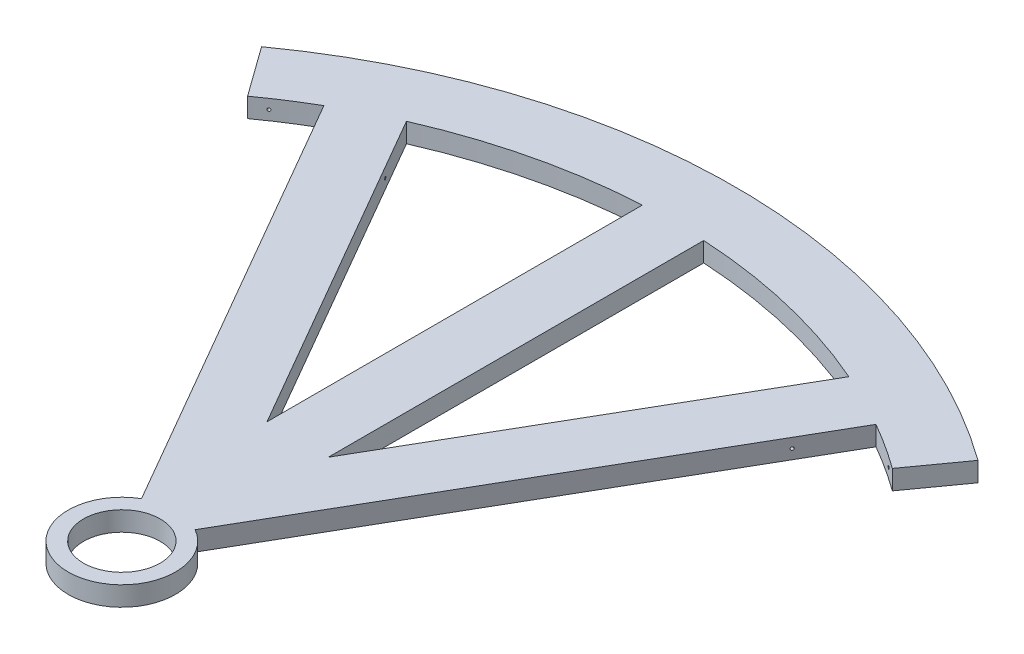
SolidWorks part; units mm, degrees
ref_plane "Front Plane" through (0, 0, 0) normal (0, 0, 1) x (1, 0, 0)
ref_plane "Top Plane" through (0, 0, 0) normal (0, 1, 0) x (1, 0, 0)
ref_plane "Right Plane" through (0, 0, 0) normal (1, 0, 0) x (0, 0, -1)
sketch "Sketch1" plane through (0, 0, 0) normal (0, 1, 0) x (1, 0, 0)
  line L0 (-90, -17.3205) -> (0, -173.2051)
  line L1 (0, -173.2051) -> (90, -17.3205)
  line L2 (-100, 0) -> (100, 0) construction
  line L3 (-72.1222, -8.2857) -> (-10, -115.8846)
  line L4 (10, -115.8846) -> (72.1222, -8.2857)
  line L5 (82.1782, 9.1318) -> (82.6795, 10)
  line L6 (0, -133.2051) -> (82.6795, 10) construction
  line L7 (-10, 6.5169) -> (-10, -115.8846)
  line L8 (10, -115.8846) -> (10, 6.5169)
  line L9 (-72.1222, -8.2857) -> (0, -133.2051) construction
  line L10 (-105.119, -27.0887) -> (-116.7988, -10.8535)
  line L11 (105.119, -27.0887) -> (116.7988, -10.8535)
  line L12 (-100, 0) -> (0, -173.2051) construction
  line L13 (0, -173.2051) -> (100, 0) construction
  arc A0 (-100, 0) -> (100, 0) centre (0, -173.2051) cw
  arc A1 (-72.1222, -8.2857) -> (-10, 6.5169) centre (0, -173.2051) cw
  arc A2 (-72.1222, -8.2857) -> (90, -17.3205) centre (0, -173.2051) cw construction
  arc A3 (10, 6.5169) -> (72.1222, -8.2857) centre (0, -173.2051) cw
  arc A4 (100, 0) -> (116.7988, -10.8535) centre (0, -173.2051) cw
  arc A5 (-100, 0) -> (-116.7988, -10.8535) centre (0, -173.2051) ccw
  arc A6 (-90, -17.3205) -> (-105.119, -27.0887) centre (0, -173.2051) ccw
  arc A7 (90, -17.3205) -> (105.119, -27.0887) centre (0, -173.2051) cw
  circle A8 centre (0, -173.2051) radius 12.5
  circle A9 centre (0, -173.2051) radius 17.5
  point P2 (0, 0)
  dimension "D6" = 20
  dimension "D9" = 25
  dimension "D10" = 35
  dimension "D1" = 60
  dimension "D2" = 200
  dimension "D4" = 10
  dimension "D5" = 10
  dimension "D3" = 20
  dimension "D7" = 20
  dimension "D8" = 20
extrude "Boss-Extrude1" add sketch "Sketch1" along normal blind 6.35 contours A9 L1 A7 L11 A4 A0 A5 L10 A6 L0 L8 A3 L4 L3 A1 L7 | L1 A9 L0 A8 | L0 A9 L1 A8
sketch "Sketch2" plane through (-75, 0, 43.3013) normal (-0.866, 0, 0.5) x (0.5, 0, 0.866)
  line L0 (-29.1, 6.35) -> (-29.1, 0) construction
  line L1 (-30, 6.35) -> (-30, 0) construction
  circle A0 centre (-10, 3.175) radius 0.5
  point P4 (-29.1, 3.175)
  dimension "D1" = 1
  dimension "D2" = 20
extrude "Cut-Extrude1" cut sketch "Sketch2" against normal blind 21
ref_plane "Plane1" through (-18.6098, 0, -28.8038) normal (-0.5427, 0, -0.8399) x (-0.8399, 0, 0.5427)
sketch "Sketch4" plane through (-18.6098, 0, -28.8038) normal (-0.5427, 0, -0.8399) x (-0.8399, 0, 0.5427)
  line L0 (102.9942, 6.35) -> (102.9942, 0) construction
  circle A0 centre (97.9942, 3.175) radius 0.5
  point P4 (102.9942, 3.175)
  dimension "D1" = 1
  dimension "D2" = 5
extrude "Cut-Extrude2" cut sketch "Sketch4" along normal through all
mirror "Mirror1" about plane through (0, 0, 0) normal (1, 0, 0) of "Cut-Extrude2", "Cut-Extrude1"
